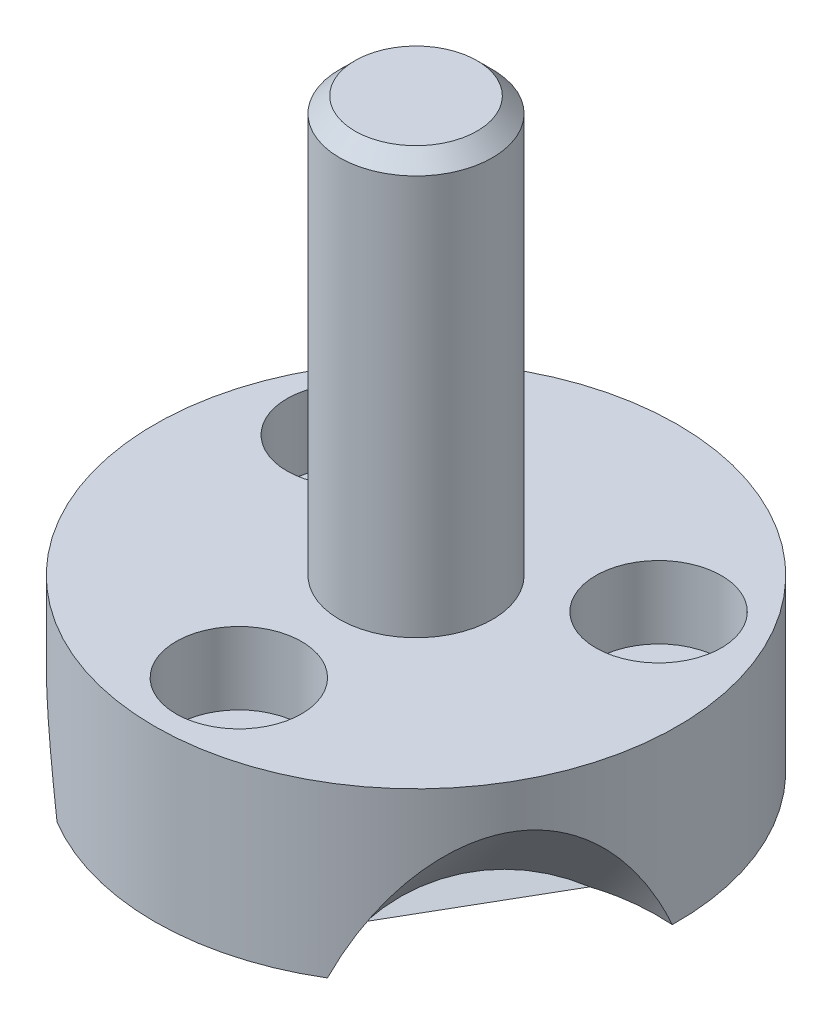
SolidWorks part; units mm, degrees
ref_plane "Front Plane" through (0, 0, 0) normal (0, 0, 1) x (1, 0, 0)
ref_plane "Top Plane" through (0, 0, 0) normal (0, 1, 0) x (1, 0, 0)
ref_plane "Right Plane" through (0, 0, 0) normal (1, 0, 0) x (0, 0, -1)
sketch "Sketch1" plane through (0, 0, 0) normal (0, 1, 0) x (1, 0, 0)
  circle A0 centre (0, 0) radius 8.5
  dimension "D1" = 17
extrude "Boss-Extrude1" add sketch "Sketch1" against normal blind 5.5
sketch "Sketch10" plane through (0, 0, 0) normal (0, 1, 0) x (1, 0, 0)
  circle A0 centre (0, 0) radius 2.485
  dimension "D1" = 4.97
extrude "Boss-Extrude3" add sketch "Sketch10" along normal blind 13.5
sketch "Sketch2" plane through (0, -5.5, 0) normal (0, -1, 0) x (-1, 0, 0)
  circle A0 centre (0, 0) radius 2.485
  dimension "D1" = 4.97
sketch "Sketch12" plane through (0, -5.5, 0) normal (0, -1, 0) x (1, 0, 0)
  circle A0 centre (0, 0) radius 4.5
  dimension "D1" = 9
extrude "Cut-Extrude4" cut sketch "Sketch12" against normal blind 2.54
chamfer "Chamfer2" distance 0.5 angle 45 1 edges at (0, 13.5, 2.485)
ref_plane "Plane1" through (0, 0, 0) normal (0, 0.7071, -0.7071) x (-1, 0, 0)
sketch "Sketch8" plane through (0, 0, 0) normal (0, 0.7071, -0.7071) x (-1, 0, 0)
  line L0 (0, 7.3701) -> (0, -19.9031) construction
  circle A0 centre (0, -15.8995) radius 5
  ellipse E1 centre (0, -3.8891) end of major axis (8.5, -3.8891) minor radius 6.0104 construction
  point P3 (0, -9.8995)
  point P11 (0, -10.8995)
  dimension "D1" = 1
  dimension "D2" = 10
sketch "Sketch14" plane through (0, 0, 0) normal (0, 1, 0) x (1, 0, 0)
  line L0 (0, 8.5) -> (0, -8.5) construction
  line L1 (0, -5.2115) -> (0, 14.0736) construction
  circle A0 centre (0, 0) radius 5.7605 construction
  circle A1 centre (0, 0) radius 8.5 construction
  circle A2 centre (0, -5.7605) radius 2.04
  circle A3 centre (-5.0339, 2.8801) radius 2.04
  circle A4 centre (4.966, 2.9193) radius 2.04
  point P19 (-0.0226, 0.013)
  dimension "D1" = 11.521
  dimension "D2" = 4.08
  dimension "D4" = 10
  dimension "D3" = 3
extrude "Cut-Extrude5" cut sketch "Sketch14" against normal blind 2.35
sketch "Sketch15" plane through (0, 0, 0) normal (0, 1, 0) x (1, 0, 0)
  circle A0 centre (4.966, 2.9193) radius 1.065
  circle A1 centre (-5.0339, 2.8801) radius 1.065
  circle A2 centre (0, -5.7605) radius 1.065
  dimension "D1" = 2.13
  dimension "D2" = 2.13
  dimension "D3" = 2.13
extrude "Cut-Extrude6" cut sketch "Sketch15" against normal through all
sketch "Sketch16" plane through (0, 0, 0) normal (0, 0.7071, -0.7071) x (-1, 0, 0)
  line L0 (0, 7.3701) -> (0, -19.9031) construction
  line L1 (0, 3.0476) -> (0, -19.745) construction
  circle A0 centre (0, -12.0104) radius 5
  ellipse E0 centre (0, 0) end of major axis (8.5, 0) minor radius 6.0104 construction
  point P7 (0, -7.0104)
  point P8 (0, -6.0104)
  dimension "D1" = 10
  dimension "D2" = 1
extrude "Cut-Extrude7" cut sketch "Sketch16" along normal blind 10
pattern_circular "CirPattern1" count 3 over 360 about axis through (0, 0, 0) along (0, 1, 0) of "Cut-Extrude7"
